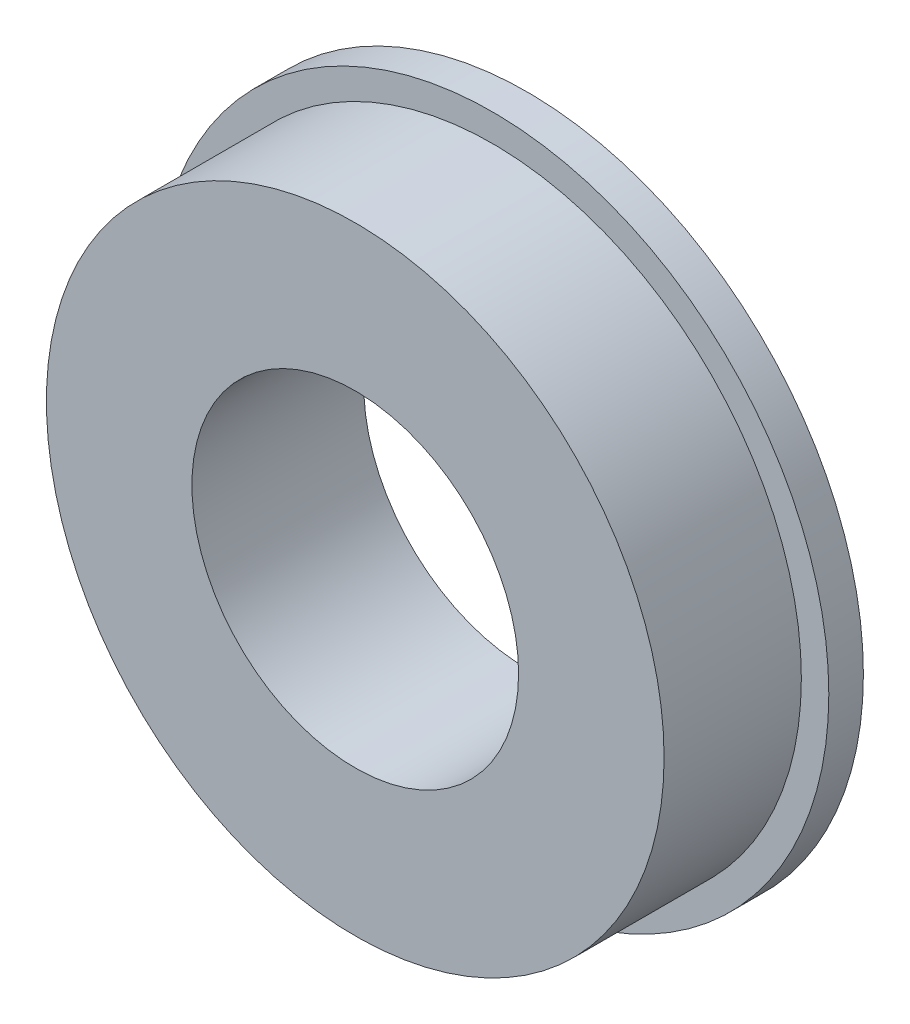
SolidWorks part; units mm, degrees
ref_plane "Front Plane" through (0, 0, 0) normal (0, 0, 1) x (1, 0, 0)
ref_plane "Top Plane" through (0, 0, 0) normal (0, 1, 0) x (1, 0, 0)
ref_plane "Right Plane" through (0, 0, 0) normal (1, 0, 0) x (0, 0, -1)
sketch "Sketch1" plane through (0, 0, 0) normal (0, 0, 1) x (1, 0, 0)
  circle A0 centre (0, 0) radius 15.5575
  dimension "D1" = 31.115
extrude "Boss-Extrude1" add sketch "Sketch1" along normal blind 1.6002
sketch "Sketch2" plane through (0, 0, 1.6002) normal (0, 0, 1) x (1, 0, 0)
  circle A0 centre (0, 0) radius 14.2875
  dimension "D1" = 28.575
extrude "Boss-Extrude2" add sketch "Sketch2" along normal blind 6.35
sketch "Sketch3" plane through (0, 0, 7.9502) normal (0, 0, 1) x (1, 0, 0)
  circle A0 centre (0, 0) radius 7.5565
  dimension "D1" = 15.113
extrude "Cut-Extrude1" cut sketch "Sketch3" against normal through all
